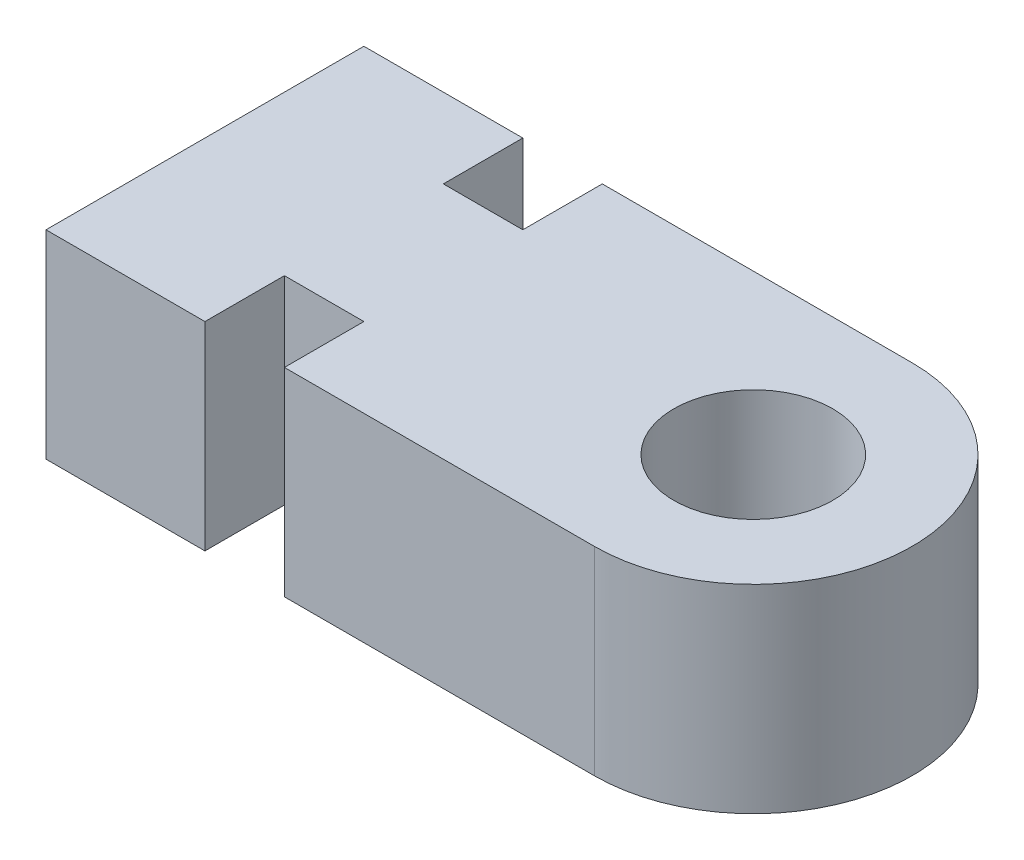
SolidWorks part; units mm, degrees
ref_plane "Front Plane" through (0, 0, 0) normal (0, 0, 1) x (1, 0, 0)
ref_plane "Top Plane" through (0, 0, 0) normal (0, 1, 0) x (1, 0, 0)
ref_plane "Right Plane" through (0, 0, 0) normal (1, 0, 0) x (0, 0, -1)
sketch "Sketch1" plane through (0, 0, 0) normal (0, 1, 0) x (1, 0, 0)
  line L0 (0, 0) -> (1597.66, 0) construction
  line L1 (0, -508) -> (0, 508)
  line L2 (0, 508) -> (508, 508)
  line L3 (0, -508) -> (508, -508)
  line L4 (508, 508) -> (508, 254)
  line L5 (508, -508) -> (508, -254)
  line L6 (508, 254) -> (762, 254)
  line L7 (508, -254) -> (762, -254)
  line L8 (762, 254) -> (762, 508)
  line L9 (762, -254) -> (762, -508)
  line L10 (762, 508) -> (1752.6, 508)
  line L11 (762, -508) -> (1752.6, -508)
  arc A0 (1752.6, 508) -> (1752.6, -508) centre (1752.6, 0) cw
  circle A1 centre (1752.6, 0) radius 254
  dimension "D1" = 254
  dimension "D4" = 508
  dimension "D6" = 508
  dimension "D2" = 508
  dimension "D3" = 254
  dimension "D5" = 1752.6
extrude "Boss-Extrude1" add sketch "Sketch1" along normal blind 635
